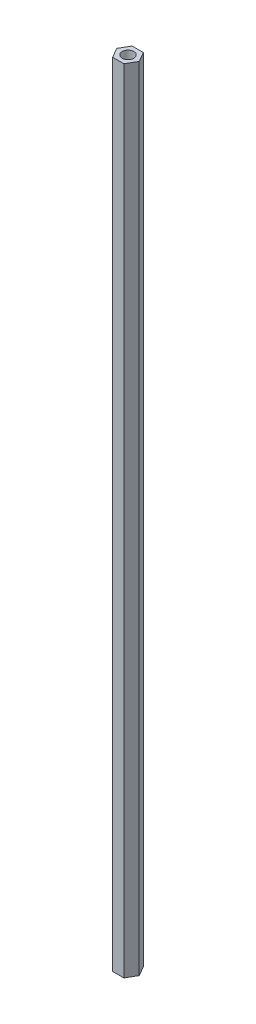
SolidWorks part; units mm, degrees
ref_plane "Front Plane" through (0, 0, 0) normal (0, 0, 1) x (1, 0, 0)
ref_plane "Top Plane" through (0, 0, 0) normal (0, 1, 0) x (1, 0, 0)
ref_plane "Right Plane" through (0, 0, 0) normal (1, 0, 0) x (0, 0, -1)
sketch "Sketch1" plane through (0, 0, 0) normal (0, 1, 0) x (1, 0, 0)
  line L1 (2.8868, 0) -> (1.4434, 2.5)
  line L2 (1.4434, 2.5) -> (-1.4434, 2.5)
  line L3 (-1.4434, 2.5) -> (-2.8868, 0)
  line L4 (-2.8868, 0) -> (-1.4434, -2.5)
  line L5 (-1.4434, -2.5) -> (1.4434, -2.5)
  line L6 (1.4434, -2.5) -> (2.8868, 0)
  circle A0 centre (0, 0) radius 2.5 construction
  dimension "D1" = 5
extrude "Boss-Extrude1" add sketch "Sketch1" along normal blind 203.2
sketch "Sketch2" plane through (0, 203.2, 0) normal (0, 1, 0) x (1, 0, 0)
  circle A0 centre (0, 0) radius 1.5
  dimension "D1" = 3
extrude "Cut-Extrude1" cut sketch "Sketch2" against normal through all
